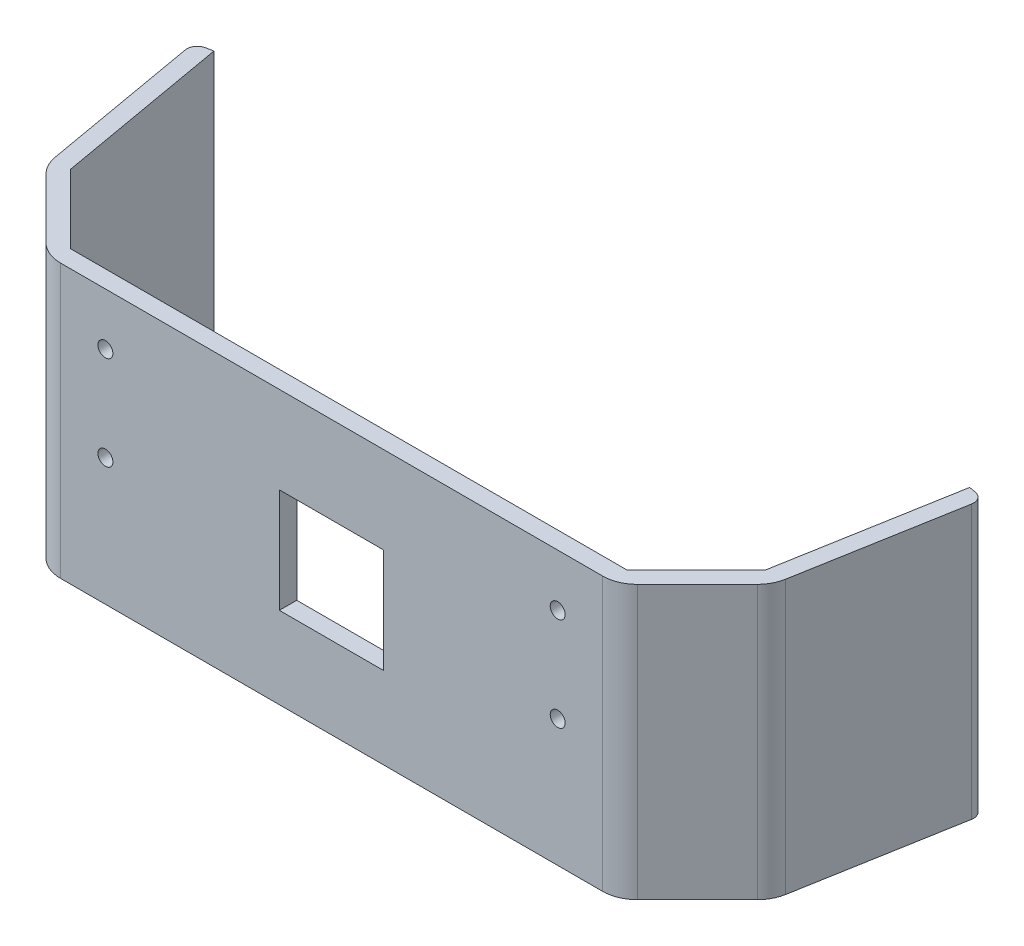
SolidWorks part; units mm, degrees
ref_plane "Front Plane" through (0, 0, 0) normal (0, 0, 1) x (1, 0, 0)
ref_plane "Top Plane" through (0, 0, 0) normal (0, 1, 0) x (1, 0, 0)
ref_plane "Right Plane" through (0, 0, 0) normal (1, 0, 0) x (0, 0, -1)
sketch "Sketch1" plane through (0, 0, 0) normal (0, 1, 0) x (1, 0, 0)
  line L0 (-80, 0) -> (80, 0)
  line L1 (80, 0) -> (99.799, 19.799)
  line L2 (99.799, 19.799) -> (108.6153, 69.799)
  line L3 (-80, 0) -> (-99.799, 19.799)
  line L4 (-99.799, 19.799) -> (-108.6153, 69.799)
  line L5 (47.7315, -170.4584) -> (207.7315, -170.4584)
  line L6 (207.7315, -170.4584) -> (227.5305, -150.6594)
  line L7 (227.5305, -150.6594) -> (236.3468, -100.6594)
  line L8 (47.7315, -170.4584) -> (27.9325, -150.6594)
  line L9 (27.9325, -150.6594) -> (19.1161, -100.6594)
  line L10 (-185.0505, -261.5314) -> (-206.4048, -140.4249)
  line L11 (-47.1234, -399.4584) -> (-185.0505, -261.5314)
  line L12 (-47.1234, -399.4584) -> (302.5864, -399.4584)
  line L13 (302.5864, -399.4584) -> (440.5134, -261.5314)
  line L14 (440.5134, -261.5314) -> (461.8678, -140.4249)
  line L15 (104.4493, 17.3782) -> (113.5394, 68.9307)
  line L16 (82.0711, -5) -> (104.4493, 17.3782)
  line L17 (-82.0711, -5) -> (82.0711, -5)
  line L18 (-82.0711, -5) -> (-104.4493, 17.3782)
  line L19 (-104.4493, 17.3782) -> (-113.5394, 68.9307)
  line L20 (-113.5394, 68.9307) -> (-108.6153, 69.799)
  line L21 (108.6153, 69.799) -> (113.5394, 68.9307)
  point P4 (0, 0)
  point P12 (127.7315, -170.4584)
  dimension "D1" = 160
  dimension "D2" = 28
  dimension "D3" = 50
  dimension "D4" = 50
  dimension "D5" = 28
  dimension "D6" = 135
  dimension "D7" = 135
  dimension "D8" = 145
  dimension "D9" = 145
  dimension "D10" = 160
  dimension "D11" = 28
  dimension "D12" = 50
  dimension "D13" = 28
  dimension "D14" = 135
  dimension "D15" = 135
  dimension "D16" = 50
  dimension "D17" = 145
  dimension "D18" = 145
  dimension "D21" = 5
  dimension "D19" = 229
  dimension "D20" = 5
extrude "Boss-Extrude1" add sketch "Sketch1" along normal blind 78.5 contours L21 L15 L16 L17 L18 L19 L20 L4 L3 L0 L1 L2
fillet "Fillet1" radius 10 1 edges at (82.0711, 39.25, 5)
fillet "Fillet2" radius 10 1 edges at (104.4493, 39.25, -17.3782)
fillet "Fillet12" radius 10 2 edges at (-82.0711, 39.25, 5) (-104.4493, 39.25, -17.3782)
fillet "Fillet13" radius 3 2 edges at (113.5394, 39.25, -68.9307) (-113.5394, 39.25, -68.9307)
sketch "Sketch2" plane through (0, 0, 5) normal (0, 0, 1) x (1, 0, 0)
  line L0 (0, 0) -> (0, 23.5)
  line L1 (0, 23.5) -> (0, 38.5)
  line L3 (-15, 53.5) -> (15, 53.5)
  line L4 (-15, 53.5) -> (-15, 23.5)
  line L5 (-15, 23.5) -> (15, 23.5)
  line L6 (15, 53.5) -> (15, 23.5)
  line L7 (-15, 53.5) -> (15, 23.5) construction
  line L8 (-15, 23.5) -> (15, 53.5) construction
  dimension "D1" = 23.5
  dimension "D2" = 15
  dimension "D3" = 30
  dimension "D4" = 30
extrude "Cut-Extrude1" cut sketch "Sketch2" against normal blind 78.5 contours L4 L3 L6 L5
ref_plane "Plane1" through (-80, 0, 0) normal (1, 0, 0) x (0, 0, -1)
sketch "Sketch4" plane through (0, 0, 5) normal (0, 0, 1) x (1, 0, 0)
  line L0 (-15, 53.5) -> (-15, 23.5) construction
  line L1 (15, 53.5) -> (15, 23.5) construction
  line L2 (-15, 23.5) -> (15, 23.5) construction
  line L4 (-77.9289, 78.5) -> (77.9289, 78.5) construction
  circle A0 centre (65, 36.5) radius 2.15
  circle A1 centre (65, 63.5) radius 2.15
  circle A2 centre (-65, 63.5) radius 2.15
  circle A3 centre (-65, 36.5) radius 2.15
  dimension "D1" = 50
  dimension "D2" = 50
  dimension "D3" = 50
  dimension "D4" = 50
  dimension "D5" = 13
  dimension "D6" = 15
  dimension "D7" = 15
  dimension "D9" = 4.3
  dimension "D10" = 4.3
  dimension "D11" = 4.3
  dimension "D12" = 4.3
  dimension "D8" = 13
extrude "Cut-Extrude2" cut sketch "Sketch4" against normal blind 78.5
